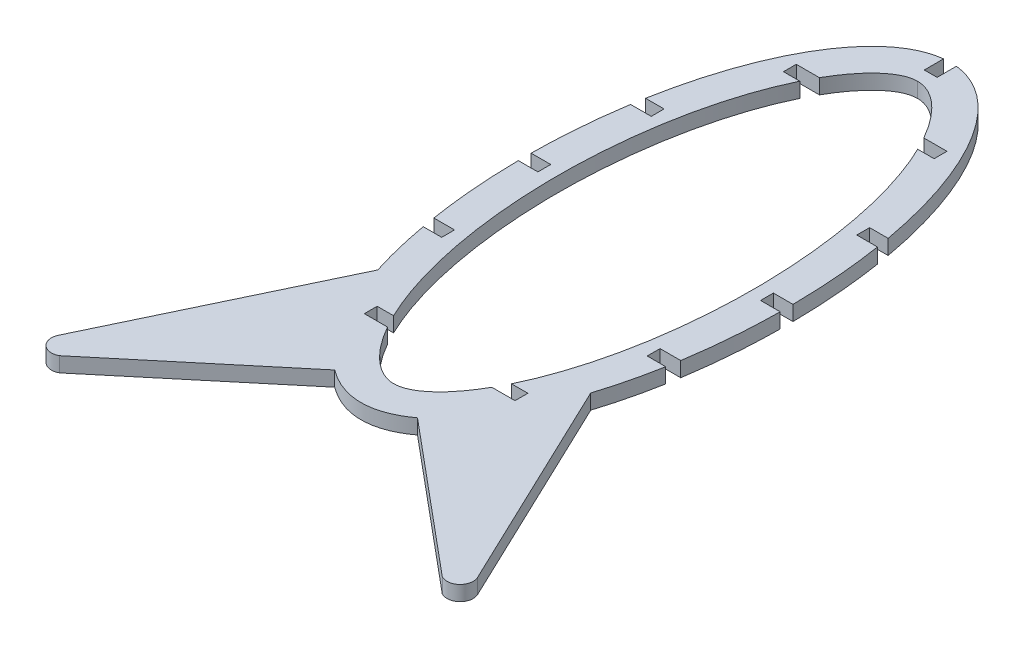
SolidWorks part; units mm, degrees
ref_plane "Front Plane" through (0, 0, 0) normal (0, 0, 1) x (1, 0, 0)
ref_plane "Top Plane" through (0, 0, 0) normal (0, 1, 0) x (1, 0, 0)
ref_plane "Right Plane" through (0, 0, 0) normal (1, 0, 0) x (0, 0, -1)
sketch "Sketch1" plane through (0, 0, 0) normal (0, 1, 0) x (1, 0, 0)
  line L2 (25.4, 0) -> (-45.1447, 0) construction
  line L3 (21.59, 0) -> (30.3971, 0) construction
  line L4 (21.59, 1.2446) -> (25.394, 1.2446)
  line L5 (21.59, 1.2446) -> (21.59, -1.2446)
  line L6 (21.59, -1.2446) -> (25.394, -1.2446)
  line L8 (37.0979, -78.485) -> (8.0291, -54.2196)
  line L9 (40.6569, -75.1899) -> (20.6588, -33.2492)
  line L10 (23.7402, 20.32) -> (29.3413, 20.32) construction
  line L11 (19.9302, 21.5646) -> (23.5224, 21.5646)
  line L12 (19.9302, 21.5646) -> (19.9302, 19.0754)
  line L13 (19.9302, 19.0754) -> (23.9434, 19.0754)
  line L19 (14.0482, 40.64) -> (-23.5224, 40.64) construction
  line L20 (0, 57.15) -> (0, 41.8846) construction
  line L21 (-37.0979, -78.485) -> (-8.0291, -54.2196)
  line L22 (-14.6132, -41.8846) -> (-10.1242, -41.8846)
  line L23 (-14.6132, -41.8846) -> (-14.6132, -39.3954)
  line L24 (-14.6132, -39.3954) -> (-11.4313, -39.3954)
  line L25 (19.9302, -21.5646) -> (23.5224, -21.5646)
  line L26 (19.9302, -21.5646) -> (19.9302, -19.0754)
  line L27 (19.9302, -19.0754) -> (23.9434, -19.0754)
  line L28 (-40.6569, -75.1899) -> (-20.6588, -33.2492)
  line L29 (14.6132, 41.8846) -> (10.1242, 41.8846)
  line L30 (14.6132, 41.8846) -> (14.6132, 39.3954)
  line L31 (14.6132, 39.3954) -> (11.4313, 39.3954)
  line L32 (-19.9302, -21.5646) -> (-23.5224, -21.5646)
  line L33 (-19.9302, -21.5646) -> (-19.9302, -19.0754)
  line L34 (-19.9302, -19.0754) -> (-23.9434, -19.0754)
  line L35 (-21.59, 1.2446) -> (-21.59, -1.2446)
  line L36 (-21.59, 1.2446) -> (-25.394, 1.2446)
  line L37 (-21.59, -1.2446) -> (-25.394, -1.2446)
  line L38 (-19.9302, 21.5646) -> (-23.5224, 21.5646)
  line L39 (-19.9302, 21.5646) -> (-19.9302, 19.0754)
  line L40 (-19.9302, 19.0754) -> (-23.9434, 19.0754)
  line L41 (14.6132, -39.3954) -> (11.4313, -39.3954)
  line L42 (-14.6132, 41.8846) -> (-10.1242, 41.8846)
  line L43 (-14.6132, 41.8846) -> (-14.6132, 39.3954)
  line L44 (-14.6132, 39.3954) -> (-11.4313, 39.3954)
  line L46 (0, 39.3954) -> (0, -57.15) construction
  line L47 (14.6132, -41.8846) -> (14.6132, -39.3954)
  line L48 (14.6132, -41.8846) -> (10.1242, -41.8846)
  line L49 (0, 57.15) -> (0, 53.34) construction
  line L51 (-1.2446, 57.0814) -> (-1.2446, 53.34)
  line L52 (-1.2446, 53.34) -> (1.2446, 53.34)
  line L53 (1.2446, 57.0814) -> (1.2446, 53.34)
  arc A0 (37.0979, -78.485) -> (40.6569, -75.1899) centre (38.3642, -76.2831) ccw
  arc A1 (-37.0979, -78.485) -> (-40.6569, -75.1899) centre (-38.3642, -76.2831) cw
  ellipse E0 centre (0, 0) end of major axis (0, 57.15) minor radius 25.4 (-23.9434, 19.0754) -> (-25.394, 1.2446) ccw
  ellipse E1 centre (0, 0) end of major axis (0, 57.15) minor radius 25.4 (-25.394, -1.2446) -> (-23.9434, -19.0754) ccw
  ellipse E2 centre (0, 0) end of major axis (0, 57.15) minor radius 25.4 (-23.5224, -21.5646) -> (-20.6588, -33.2492) ccw
  ellipse E3 centre (0, 0) end of major axis (0, 57.15) minor radius 25.4 (23.9434, -19.0754) -> (25.394, -1.2446) ccw
  ellipse E4 centre (0, 0) end of major axis (0, 57.15) minor radius 25.4 (25.394, 1.2446) -> (23.9434, 19.0754) ccw
  ellipse E5 centre (0, 0) end of major axis (0, 57.15) minor radius 25.4 (23.5224, 21.5646) -> (1.2446, 57.0814) ccw
  ellipse E6 centre (0, 0) end of major axis (0, 57.15) minor radius 25.4 (-1.2446, 57.0814) -> (-23.5224, 21.5646) ccw
  ellipse E7 centre (0, 0) end of major axis (0, 57.15) minor radius 25.4 (-8.0291, -54.2196) -> (8.0291, -54.2196) ccw
  ellipse E8 centre (0, 0) end of major axis (0, 57.15) minor radius 25.4 (20.6588, -33.2492) -> (23.5224, -21.5646) ccw
  spline S0 degree 3 poles (10.1242, 41.8846) (9.6963, 42.6376) (8.1175, 45.2063) (5.3181, 48.5143) (2.7404, 50.1903) (1.0874, 50.7223) (0.3742, 50.8) (0, 50.8) knots -0.663564 -0.663564 -0.663564 -0.663564 -0.589049 -0.392699 -0.19635 -0.098175 0 0 0 0
  spline S1 degree 3 poles (0, -50.8) (0.3742, -50.8) (1.0874, -50.7223) (2.7404, -50.1903) (5.3181, -48.5143) (8.1175, -45.2063) (9.6963, -42.6376) (10.1242, -41.8846) knots -3.141593 -3.141593 -3.141593 -3.141593 -3.043418 -2.945243 -2.748894 -2.552544 -2.478028 -2.478028 -2.478028 -2.478028
  spline S2 degree 3 poles (0, -50.8) (-0.3742, -50.8) (-1.0874, -50.7223) (-2.7404, -50.1903) (-5.3181, -48.5143) (-8.1175, -45.2063) (-9.6963, -42.6376) (-10.1242, -41.8846) knots -3.141593 -3.141593 -3.141593 -3.141593 -3.043418 -2.945243 -2.748894 -2.552544 -2.478028 -2.478028 -2.478028 -2.478028
  spline S3 degree 3 poles (-10.1242, 41.8846) (-9.6963, 42.6376) (-8.1175, 45.2063) (-5.3181, 48.5143) (-2.7404, 50.1903) (-1.0874, 50.7223) (-0.3742, 50.8) (0, 50.8) knots -0.663564 -0.663564 -0.663564 -0.663564 -0.589049 -0.392699 -0.19635 -0.098175 0 0 0 0
  spline S4 degree 3 poles (-11.4313, -39.3954) (-11.6771, -38.8896) (-12.9878, -36.0709) (-15.1482, -30.1662) (-18.0998, -17.7755) (-19.6835, 0) (-18.0998, 17.7755) (-15.1482, 30.1662) (-12.9878, 36.0709) (-11.6771, 38.8896) (-11.4313, 39.3954) knots -2.400746 -2.400746 -2.400746 -2.400746 -2.356194 -2.159845 -1.963495 -1.570796 -1.178097 -0.981748 -0.785398 -0.740847 -0.740847 -0.740847 -0.740847
  spline S5 degree 3 poles (11.4313, -39.3954) (11.6771, -38.8896) (12.9878, -36.0709) (15.1482, -30.1662) (18.0998, -17.7755) (19.6835, 0) (18.0998, 17.7755) (15.1482, 30.1662) (12.9878, 36.0709) (11.6771, 38.8896) (11.4313, 39.3954) knots -2.400746 -2.400746 -2.400746 -2.400746 -2.356194 -2.159845 -1.963495 -1.570796 -1.178097 -0.981748 -0.785398 -0.740847 -0.740847 -0.740847 -0.740847
  point P25 (19.9302, 20.32)
  point P35 (44.1664, -82.55)
  dimension "D5" = 2.54
  dimension "D1" = 114.3
  dimension "D2" = 25.4
  dimension "D4" = 2.4892
  dimension "D6" = 3.81
  dimension "D7" = 2.4892
  dimension "D9" = 3.81
  dimension "D3" = 25.4
  dimension "D10" = 2.4892
  dimension "D12" = 3.81
extrude "Boss-Extrude2" add sketch "Sketch1" along normal blind 2.8956
equation "\"slot_width\" = 0.098"
equation "\"slot_depth\"= 0.15"
equation "\"body_height\"= 4.5"
equation "\"fin_height\"= 1"
equation "\"gap_distance\"= 0.8"
equation "\"D1@Sketch1\"=\"body_height\""
equation "\"D4@Sketch1\"=\"slot_width\""
equation "\"D6@Sketch1\"=\"slot_depth\""
equation "\"D7@Sketch1\"=\"slot_width\""
equation "\"D9@Sketch1\"=\"slot_depth\""
equation "\"D10@Sketch1\"=\"slot_width\""
equation "\"D12@Sketch1\"=\"slot_depth\""
equation "\"D3@Sketch1\"=\"fin_height\""
